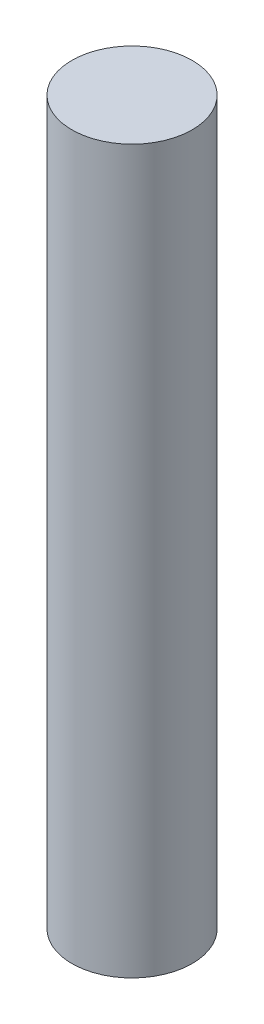
SolidWorks part; units mm, degrees
ref_plane "Alzado" through (0, 0, 0) normal (0, 0, 1) x (1, 0, 0)
ref_plane "Planta" through (0, 0, 0) normal (0, 1, 0) x (1, 0, 0)
ref_plane "Vista lateral" through (0, 0, 0) normal (1, 0, 0) x (0, 0, -1)
sketch "Croquis1" plane through (0, 0, 0) normal (0, 0, 1) x (1, 0, 0)
  line L0 (0, 0) -> (0, 300)
  line L1 (0, 300) -> (-25, 300)
  line L2 (-25, 300) -> (-25, 0)
  line L3 (-25, 0) -> (0, 0)
  dimension "D1" = 300
  dimension "D2" = 25
revolve "Revolución1" add sketch "Croquis1" angle 360 about L0
